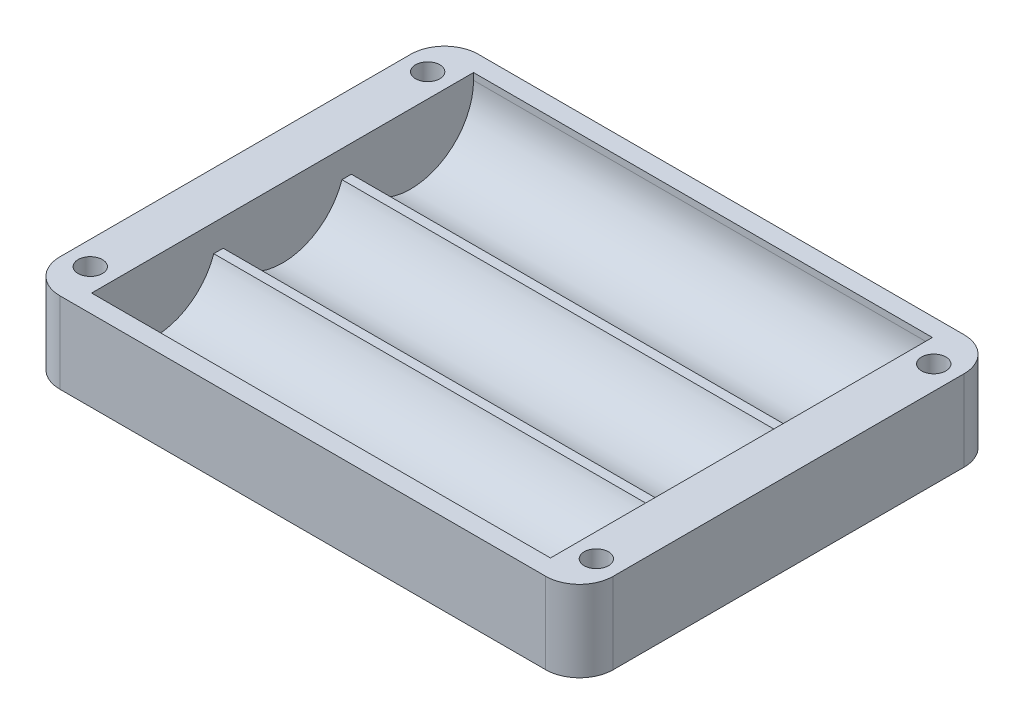
SolidWorks part; units mm, degrees
ref_plane "Front Plane" through (0, 0, 0) normal (0, 0, 1) x (1, 0, 0)
ref_plane "Top Plane" through (0, 0, 0) normal (0, 1, 0) x (1, 0, 0)
ref_plane "Right Plane" through (0, 0, 0) normal (1, 0, 0) x (0, 0, -1)
sketch "Sketch1" plane through (0, 0, 0) normal (0, 1, 0) x (1, 0, 0)
  line L1 (-36, 31) -> (36, 31)
  line L2 (-41, 26) -> (-41, -26)
  line L3 (-36, -31) -> (36, -31)
  line L4 (41, 26) -> (41, -26)
  line L5 (-41, 31) -> (41, -31) construction
  line L6 (-41, -31) -> (41, 31) construction
  arc A0 (36, -31) -> (41, -26) centre (36, -26) ccw
  arc A1 (36, 31) -> (41, 26) centre (36, 26) cw
  arc A2 (-41, -26) -> (-36, -31) centre (-36, -26) ccw
  arc A3 (-36, 31) -> (-41, 26) centre (-36, 26) ccw
  point P0 (0, 0)
  dimension "D3" = 5
  dimension "D1" = 82
  dimension "D2" = 62
extrude "Boss-Extrude1" add sketch "Sketch1" along normal blind 12
sketch "Sketch2" plane through (0, 0, 0) normal (1, 0, 0) x (0, 0, -1)
  line L0 (0, 0) -> (0, 38.8117) construction
  line L1 (-10.1972, 8) -> (-8.8028, 8)
  line L2 (8.8028, 8) -> (10.1972, 8)
  line L3 (-28.3, 11) -> (-28.3, 17.8664)
  line L4 (-28.3, 17.8664) -> (28.3, 17.8664)
  line L5 (28.3, 17.8664) -> (28.3, 11)
  circle A0 centre (0, 11) radius 9.3 construction
  circle A1 centre (-19, 11) radius 9.3 construction
  circle A2 centre (19, 11) radius 9.3 construction
  arc A3 (-8.8028, 8) -> (8.8028, 8) centre (0, 11) ccw
  arc A4 (10.1972, 8) -> (28.3, 11) centre (19, 11) ccw
  arc A5 (-28.3, 11) -> (-10.1972, 8) centre (-19, 11) ccw
  dimension "D2" = 18.6
  dimension "D1" = 19
  dimension "D3" = 11
  dimension "D4" = 3
extrude "Cut-Extrude1" cut sketch "Sketch2" against normal mid plane 68
hole_wizard "Ø3.6 (3.6) Diameter Hole1" positions "Sketch3" profile "Sketch5" hole size "Ø3.6" standard "ANSI Metric"
sketch "Sketch3" plane through (0, 12, 0) normal (0, 1, 0) x (1, 0, 0)
  line L0 (-37.5, 25) -> (-37.5, -25) construction
  line L1 (-37.5, -25) -> (37.5, -25) construction
  line L2 (37.5, -25) -> (37.5, 25) construction
  line L3 (37.5, 25) -> (-37.5, 25) construction
  point P0 (-37.5, 25)
  point P3 (-37.5, -25)
  point P5 (37.5, -25)
  point P7 (37.5, 25)
  point P20 (0, 25)
  point P22 (0, -25)
  point P23 (37.5, 0)
  point P24 (-37.5, 0)
  dimension "D1" = 50
  dimension "D2" = 75
sketch "Sketch5" plane through (-37.5, 12, -25) normal (1, 0, 0) x (0, 0, 1)
  line L0 (0, 0) -> (0, 11.0815)
  line L1 (0, 11.0815) -> (1.8, 10)
  line L2 (1.8, 10) -> (1.8, 0)
  line L5 (1.8, 0) -> (0, 0)
  line L10 (0, 11.0815) -> (-1.8, 10) construction
  line L11 (0, -6.35) -> (0, 107.95) construction
  dimension "Hole Dia." = 3.6
  dimension "Hole Depth" = 10
  dimension "Drill Angle" = 118
